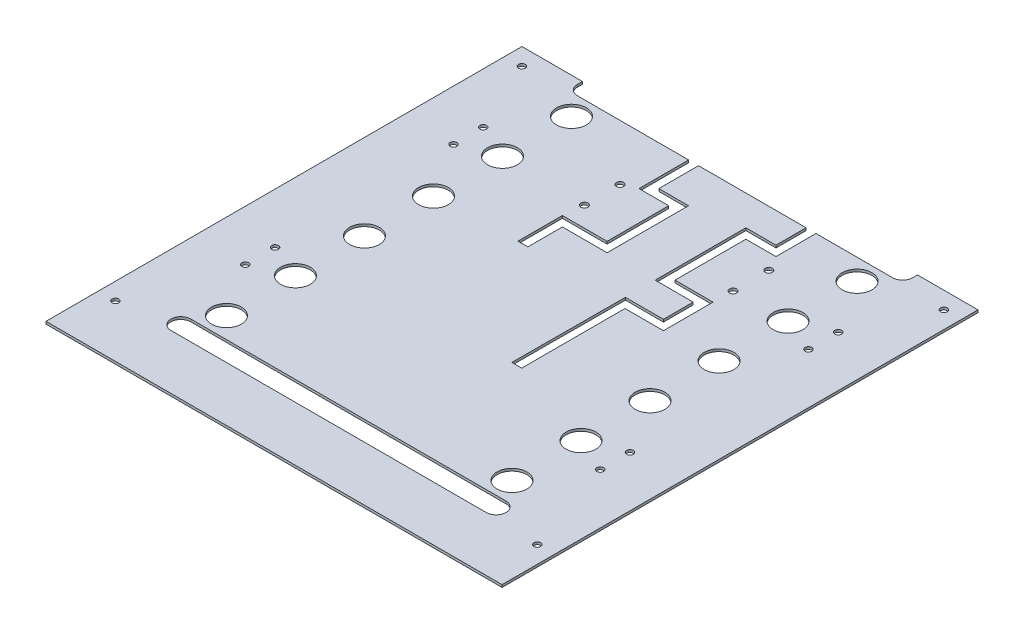
SolidWorks part; units mm, degrees
material "PC High Viscosity"
ref_plane "Front Plane" through (0, 0, 0) normal (0, 0, 1) x (1, 0, 0)
ref_plane "Top Plane" through (0, 0, 0) normal (0, 1, 0) x (1, 0, 0)
ref_plane "Right Plane" through (0, 0, 0) normal (1, 0, 0) x (0, 0, -1)
sketch "Sketch1" plane through (0, 0, 0) normal (0, 1, 0) x (1, 0, 0)
  line L0 (-100.965, -111.125) -> (100.965, -111.125) construction
  line L1 (-146.05, 152.4) -> (146.05, 152.4)
  line L2 (-146.05, 152.4) -> (-146.05, -152.4)
  line L3 (-146.05, -152.4) -> (146.05, -152.4)
  line L4 (146.05, 152.4) -> (146.05, -152.4)
  line L5 (-146.05, 152.4) -> (146.05, -152.4) construction
  line L6 (-146.05, -152.4) -> (146.05, 152.4) construction
  line L7 (-100.965, -104.775) -> (100.965, -104.775)
  line L8 (-100.965, -117.475) -> (100.965, -117.475)
  line L9 (-100.965, 149.225) -> (100.965, 149.225) construction
  line L10 (-100.965, 155.575) -> (100.965, 155.575)
  line L11 (-100.965, 142.875) -> (100.965, 142.875)
  line L12 (-107.315, 149.225) -> (-107.315, 155.575)
  line L13 (-107.315, 155.575) -> (-100.965, 155.575)
  line L14 (107.315, 149.225) -> (107.315, 155.575)
  line L15 (107.315, 155.575) -> (100.965, 155.575)
  line L16 (-135.128, 141.478) -> (135.128, 141.478) construction
  line L17 (-113.665, 95.25) -> (-113.665, 76.2) construction
  line L18 (-91.44, 41.148) -> (-91.44, -3.048) construction
  line L19 (91.44, 41.148) -> (91.44, -3.048) construction
  line L20 (-91.44, 19.05) -> (91.44, 19.05) construction
  line L21 (0, 149.225) -> (0, -111.125) construction
  arc A0 (-100.965, -104.775) -> (-100.965, -117.475) centre (-100.965, -111.125) ccw
  arc A1 (100.965, -117.475) -> (100.965, -104.775) centre (100.965, -111.125) ccw
  arc A2 (-100.965, 155.575) -> (-100.965, 142.875) centre (-100.965, 149.225) ccw
  arc A3 (100.965, 142.875) -> (100.965, 155.575) centre (100.965, 149.225) ccw
  circle A4 centre (-135.128, 141.478) radius 2.1527
  circle A5 centre (-135.128, -118.872) radius 2.1527
  circle A6 centre (135.128, 141.478) radius 2.1527
  circle A7 centre (135.128, -118.872) radius 2.1527
  circle A8 centre (-91.44, 129.54) radius 9.525
  circle A9 centre (91.44, 129.54) radius 9.525
  circle A10 centre (91.44, 85.344) radius 9.525
  circle A11 centre (-91.44, 85.344) radius 9.525
  circle A12 centre (91.44, 41.148) radius 9.525
  circle A13 centre (-91.44, 41.148) radius 9.525
  circle A14 centre (91.44, -3.048) radius 9.525 construction
  circle A15 centre (-91.44, -3.048) radius 9.525 construction
  circle A16 centre (91.44, -47.244) radius 9.525
  circle A17 centre (-91.44, -47.244) radius 9.525
  circle A18 centre (91.44, -91.44) radius 9.525
  circle A19 centre (-91.44, -91.44) radius 9.525
  circle A20 centre (-91.44, -3.048) radius 9.525
  circle A21 centre (91.44, -3.048) radius 9.525
  circle A22 centre (-113.665, 95.25) radius 2.1527
  circle A23 centre (-113.665, 76.2) radius 2.1527
  circle A24 centre (-113.665, -38.1) radius 2.1527
  circle A25 centre (-113.665, -57.15) radius 2.1527
  circle A26 centre (113.665, -57.15) radius 2.1527
  circle A27 centre (113.665, -38.1) radius 2.1527
  circle A28 centre (113.665, 76.2) radius 2.1527
  circle A29 centre (113.665, 95.25) radius 2.1527
  point P0 (0, 0)
  point P8 (0, -111.125)
  point P13 (0, -111.125)
  point P14 (0, -152.4)
  point P17 (0, 149.225)
  point P37 (0, 141.478)
  point P83 (0, 0)
  dimension "D4" = 6.35
  dimension "D9" = 4.3053
  dimension "D11" = 19.05
  dimension "D17" = 19.05
  dimension "D18" = 4.3053
  dimension "D1" = 292.1
  dimension "D2" = 304.8
  dimension "D3" = 45.085
  dimension "D5" = 41.275
  dimension "D6" = 3.175
  dimension "D7" = 10.922
  dimension "D8" = 10.922
  dimension "D10" = 33.528
  dimension "D12" = 54.61
  dimension "D13" = 22.86
  dimension "D14" = 54.61
  dimension "D16" = 44.196
  dimension "D19" = 22.225
  dimension "D20" = 19.05
  dimension "D21" = 9.906
  dimension "D15" = 6
extrude "Boss-Extrude1" add sketch "Sketch1" along normal blind 1.5875 contours A3 L11 A2 L12 L1 L2 L3 L4 L14 A1 L8 A0 L7
sketch "Sketch2" plane through (0, 1.5875, 0) normal (0, 1, 0) x (1, 0, 0)
  line L0 (-100.965, 142.875) -> (100.965, 142.875) construction
  line L2 (-29.7634, 142.875) -> (-29.7634, 111.1064)
  line L3 (-29.7634, 111.1064) -> (-23.4134, 111.1064)
  line L4 (-23.4134, 142.875) -> (-23.4134, 117.4564)
  line L5 (146.05, 152.4) -> (146.05, -152.4) construction
  line L6 (-23.4134, 117.4564) -> (-4.3951, 117.4564)
  line L7 (-29.7634, 116.1864) -> (-29.7634, 111.1064)
  line L8 (-29.7634, 111.1064) -> (-10.7451, 111.1064)
  line L9 (-4.3951, 117.4564) -> (-4.3951, 111.1064)
  line L11 (-10.7451, 111.1064) -> (-10.7451, 80.774)
  line L13 (-4.3951, 111.1064) -> (-4.3951, 74.424)
  line L19 (-39.37, 54.6179) -> (-39.37, 43.18)
  line L20 (-39.37, 43.18) -> (-33.02, 43.18)
  line L21 (-33.02, 54.6179) -> (-33.02, 43.18)
  line L26 (-29.7634, 142.875) -> (-23.4134, 142.875)
  line L28 (45.4686, 142.875) -> (45.4686, 123.5982)
  line L30 (51.8186, 142.875) -> (51.8186, 116.1864)
  line L65 (25.908, -26.035) -> (32.258, -26.035)
  line L66 (32.258, -3.9197) -> (32.258, -6.1487)
  line L86 (-4.3951, 74.424) -> (-4.3951, 82.044)
  line L87 (45.4686, 123.5982) -> (26.1969, 123.5982)
  line L88 (51.8186, 116.1864) -> (51.8186, 117.2482)
  line L90 (26.1969, 123.5982) -> (26.1969, 117.2482)
  line L91 (25.908, -26.035) -> (32.258, -26.035)
  line L143 (26.1969, 117.2482) -> (26.1969, 65.498)
  line L144 (26.1969, 65.498) -> (50.5486, 65.498)
  line L145 (45.4686, 142.875) -> (51.8186, 142.875)
  line L146 (50.5486, 65.498) -> (50.5486, 46.448)
  line L167 (50.5486, 46.448) -> (26.1969, 46.448)
  line L168 (-23.4134, 111.1064) -> (-10.7451, 111.1064)
  line L169 (-4.3951, 74.424) -> (-4.3951, 65.2978)
  line L171 (26.1969, 46.448) -> (25.908, -26.035)
  line L173 (32.258, -26.035) -> (32.258, 40.098)
  line L179 (-39.37, 54.6179) -> (-39.37, 43.18)
  line L180 (-39.37, 43.18) -> (-33.02, 43.18)
  line L181 (-33.02, 54.6179) -> (-33.02, 43.18)
  line L182 (32.258, 40.098) -> (56.8986, 40.098)
  line L183 (56.8986, 40.098) -> (56.8986, 71.848)
  line L184 (56.8986, 71.848) -> (32.5469, 71.848)
  line L185 (32.5469, 117.2482) -> (32.5469, 71.848)
  line L186 (51.8186, 117.2482) -> (32.5469, 117.2482)
  line L187 (-4.3951, 65.2978) -> (-33.02, 65.2978)
  line L188 (-33.02, 65.2978) -> (-33.02, 54.6179)
  line L189 (-39.37, 54.6179) -> (-39.37, 71.6478)
  line L190 (-39.37, 71.6478) -> (-10.7451, 71.6478)
  line L191 (-10.7451, 71.6478) -> (-10.7451, 80.774)
  line L192 (-4.3951, 74.424) -> (-4.3951, 65.2978)
  line L193 (107.315, 152.4) -> (146.05, 152.4) construction
  point P17 (38.3728, 65.498)
  dimension "D2" = 6.35
  dimension "D3" = 99.695
  dimension "D4" = 6.35
  dimension "D5" = 6.35
  dimension "D6" = 6.35
  dimension "D7" = 6.35
  dimension "D8" = 25.4
  dimension "D9" = 113.792
  dimension "D10" = 6.35
  dimension "D11" = 6.35
  dimension "D12" = 6.35
  dimension "D13" = 6.35
  dimension "D14" = 19.05
  dimension "D15" = 6.35
  dimension "D16" = 6.35
  dimension "D17" = 6.35
  dimension "D18" = 30.3324
  dimension "D19" = 178.435
  dimension "D20" = 6.35
  dimension "D21" = 6.35
extrude "Cut-Extrude1" cut sketch "Sketch2" against normal blind 2.54
sketch "Sketch4" plane through (0, 0, 0) normal (0, -1, 0) x (1, 0, 0)
  line L0 (-146.05, -152.4) -> (-146.05, 152.4) construction
  line L1 (-100.965, -142.875) -> (-29.7634, -142.875) construction
  line L2 (51.8186, -142.875) -> (100.965, -142.875) construction
  point P0 (-38.1, -84.455)
  point P1 (-38.1, -107.315)
  point P2 (57.15, -84.455)
  point P3 (57.15, -107.315)
  dimension "D1" = 95.25
  dimension "D2" = 22.86
  dimension "D3" = 95.25
  dimension "D4" = 107.95
  dimension "D5" = 35.56
  dimension "D6" = 22.86
  dimension "D7" = 35.56
hole_wizard "13/64 (0.18) Diameter Hole1" positions "Sketch5" profile "Sketch6" hole size "13/64" standard "ANSI Inch" end condition through all
sketch "Sketch5" plane through (0, 0, 0) normal (0, -1, 0) x (-1, 0, 0)
  point P0 (-57.15, 107.315)
  point P3 (-57.15, 84.455)
  point P6 (38.1, 84.455)
  point P9 (38.1, 107.315)
sketch "Sketch6" plane through (57.15, 0, -107.315) normal (1, 0, 0) x (0, 0, -1)
  line L0 (0, 0) -> (0, 1.5875)
  line L1 (0, 1.5875) -> (2.286, 1.5875)
  line L2 (2.286, 1.5875) -> (2.286, 0)
  line L5 (2.286, 0) -> (0, 0)
  line L11 (0, -6.35) -> (0, 107.95) construction
  dimension "Thru Hole Dia." = 4.572
  dimension "Thru Hole Depth" = 1.5875
